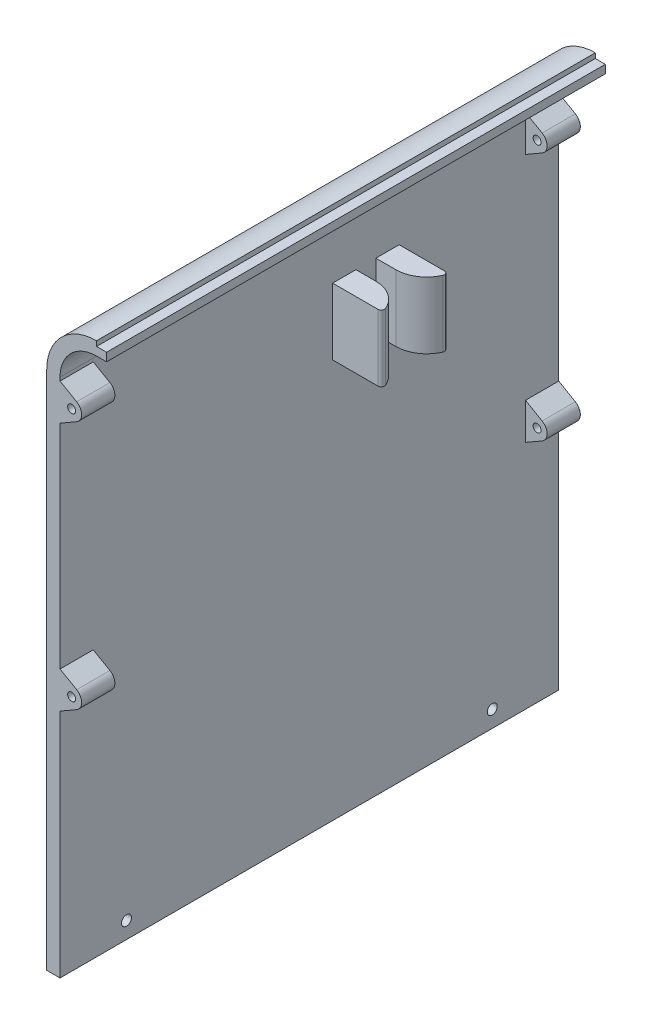
SolidWorks part; units mm, degrees
material "ABS"
ref_plane "Plan de face" through (0, 0, 0) normal (0, 0, 1) x (1, 0, 0)
ref_plane "Plan de dessus" through (0, 0, 0) normal (0, 1, 0) x (1, 0, 0)
ref_plane "Plan de droite" through (0, 0, 0) normal (1, 0, 0) x (0, 0, -1)
sketch "Esquisse1" plane through (0, 0, 0) normal (0, 0, 1) x (1, 0, 0)
  line L0 (0, 0) -> (0, 156.5)
  arc A0 (0, 156.5) -> (15, 171.5) centre (15, 156.5) cw
  dimension "D1" = 15
  dimension "D2" = 171.5
extrude "Extru.-Mince1" add sketch "Esquisse1" along normal mid plane 150 thin
sketch "Esquisse2" plane through (0, 0, 0) normal (-1, 0, 0) x (0, 0, 1)
  line L0 (0, 0) -> (0, 156.5) construction
  line L1 (75, 156.5) -> (-75, 156.5) construction
  line L2 (75, 0) -> (-75, 0) construction
  circle A0 centre (-55, 5) radius 1.5
  circle A1 centre (55, 5) radius 1.5
  dimension "D1" = 110
  dimension "D2" = 3
  dimension "D3" = 5
extrude "Enlèv. mat.-Extru.1" cut sketch "Esquisse2" against normal through all
sketch "Esquisse3" plane through (0, 0, 75) normal (0, 0, 1) x (1, 0, 0)
  line L1 (15, 167.5) -> (18, 167.5)
  line L2 (15, 167.5) -> (15, 170)
  line L3 (15, 170) -> (18, 170)
  line L4 (18, 167.5) -> (18, 170)
  dimension "D1" = 1.5
  dimension "D2" = 3
extrude "Boss.-Extru.1" add sketch "Esquisse3" against normal up to surface (150 mm away) up to face at (5.4359, 109.5641, -75)
sketch "Esquisse4" plane through (0, 0, 75) normal (0, 0, 1) x (1, 0, 0)
  line L0 (4, 155.4848) -> (9, 152.5981)
  line L1 (4, 0) -> (4, 156.5) construction
  line L2 (9, 147.4019) -> (4, 144.5152)
  line L3 (4, 144.5152) -> (4, 155.4848)
  line L4 (0, 0) -> (0, 156.5) construction
  line L5 (4, 0) -> (0, 0) construction
  arc A0 (9, 152.5981) -> (9, 147.4019) centre (7.5, 150) cw
  circle A1 centre (7.5, 150) radius 1.2
  point P10 (4, 150)
  dimension "D1" = 7.5
  dimension "D2" = 2.4
  dimension "D3" = 3
  dimension "D5" = 150
  dimension "D4" = 60
extrude "Boss.-Extru.2" add sketch "Esquisse4" against normal blind 10
mirror "Symétrie1" about plane through (0, 0, 0) normal (0, 0, 1) of "Boss.-Extru.2"
pattern_linear "Répétition linéaire1" count 2 spacing 75 along (0, -1, 0) of "Symétrie1", "Boss.-Extru.2"
sketch "Esquisse5" plane through (0, 0, 0) normal (0, -1, 0) x (1, 0, 0)
  line L0 (4, -14) -> (10, -14)
  line L1 (4, 75) -> (4, -75) construction
  line L2 (19, -7) -> (4, -7)
  line L3 (4, 75) -> (4, -75) construction
  line L4 (4, -7) -> (4, -14)
  line L5 (4, -17) -> (19, -17) construction
  line L6 (4, -27) -> (4, -20)
  line L7 (19, -27) -> (4, -27)
  line L8 (4, -20) -> (10, -20)
  arc A0 (10, -14) -> (19, -7) centre (10, -4.7143) ccw
  arc A1 (10, -20) -> (19, -27) centre (10, -29.2857) cw
  dimension "D1" = 6
  dimension "D4" = 9.2857
  dimension "D2" = 6
  dimension "D3" = 15
  dimension "D5" = 17
  dimension "D6" = 20
extrude "Boss.-Extru.3" add sketch "Esquisse5" against normal blind 20 from offset 120 offset against normal yes
fillet "Congé1" radius 1 2 edges at (19, 130, -7) (19, 130, -27)
